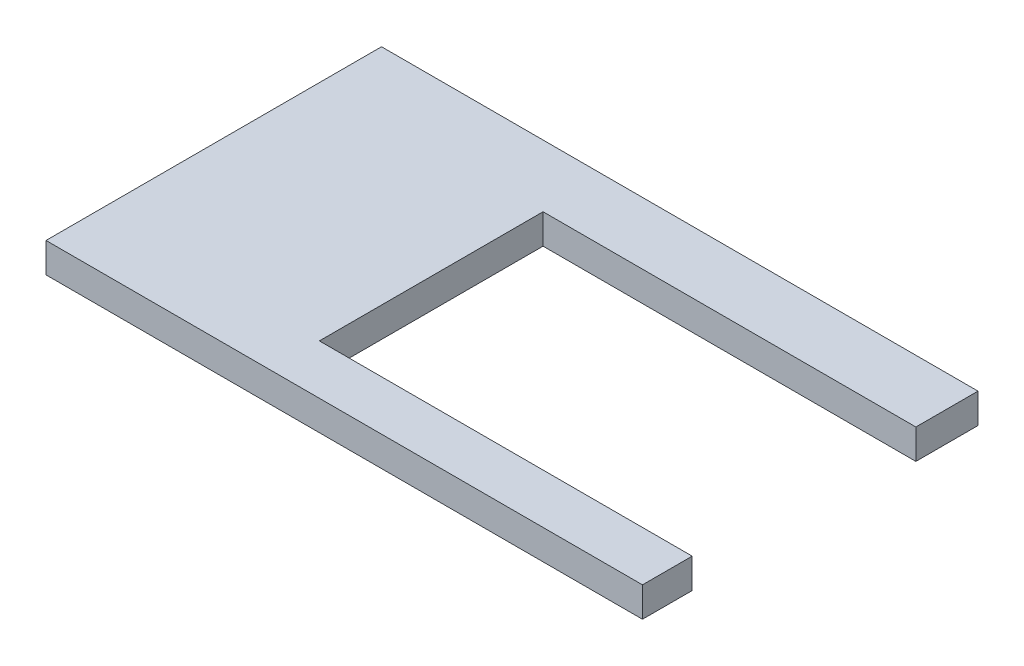
SolidWorks part; units mm, degrees
material "ABS"
ref_plane "Front Plane" through (0, 0, 0) normal (0, 0, 1) x (1, 0, 0)
ref_plane "Top Plane" through (0, 0, 0) normal (0, 1, 0) x (1, 0, 0)
ref_plane "Right Plane" through (0, 0, 0) normal (1, 0, 0) x (0, 0, -1)
sketch "Sketch1" plane through (0, 0, 0) normal (0, 1, 0) x (1, 0, 0)
  line L0 (5.715, 5.3975) -> (5.715, -6.0325)
  line L1 (5.715, 8.5725) -> (-5.715, 8.5725)
  line L2 (5.715, 8.5725) -> (5.715, -8.5725)
  line L3 (5.715, -8.5725) -> (-5.715, -8.5725)
  line L4 (-5.715, 8.5725) -> (-5.715, -8.5725)
  line L5 (5.715, 8.5725) -> (-5.715, -8.5725) construction
  line L6 (5.715, -8.5725) -> (-5.715, 8.5725) construction
  line L7 (5.715, 8.5725) -> (24.765, 8.5725)
  line L8 (5.715, 8.5725) -> (5.715, 5.3975)
  line L9 (5.715, 5.3975) -> (24.765, 5.3975)
  line L10 (24.765, 8.5725) -> (24.765, 5.3975)
  line L12 (5.715, -6.0325) -> (24.765, -6.0325)
  line L13 (5.715, -6.0325) -> (5.715, -8.5725)
  line L14 (5.715, -8.5725) -> (24.765, -8.5725)
  line L15 (24.765, -6.0325) -> (24.765, -8.5725)
  point P0 (0, 0)
  dimension "D1" = 11.43
  dimension "D2" = 3.175
  dimension "D3" = 2.54
  dimension "D4" = 17.145
  dimension "D5" = 11.43
  dimension "D6" = 19.05
  dimension "D7" = 19.05
extrude "Boss-Extrude1" add sketch "Sketch1" along normal blind 1.524 contours L15 L12 L2 L13 L14 | L1 L4 L3 L2 L0 | L10 L7 L2 L9
